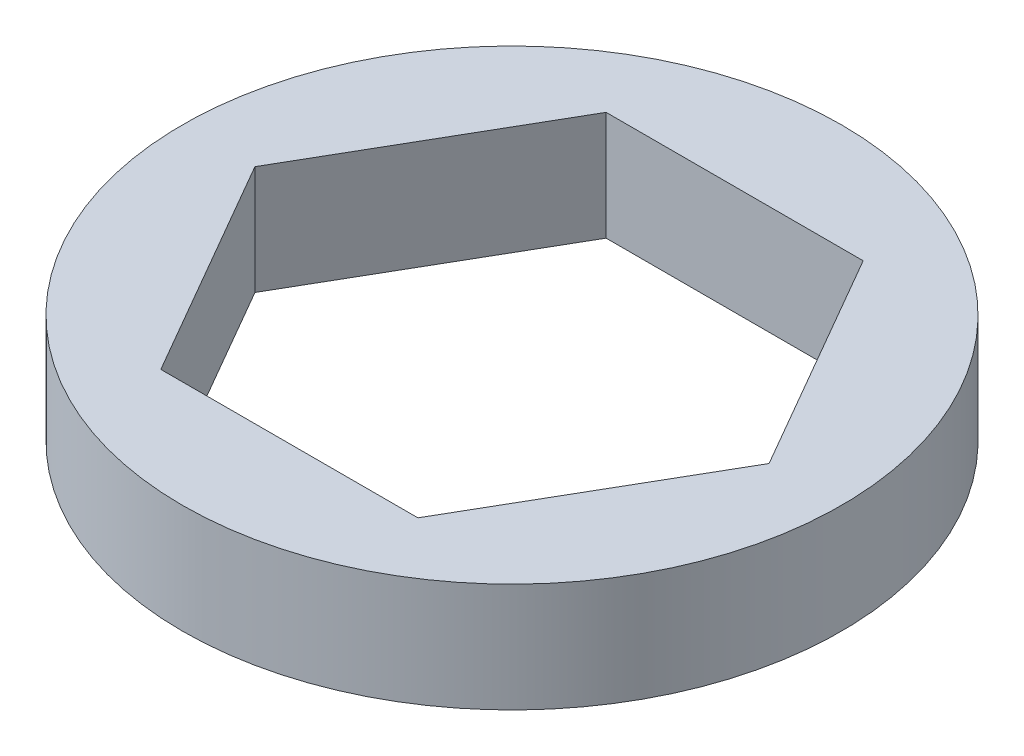
SolidWorks part; units mm, degrees
ref_plane "Front Plane" through (0, 0, 0) normal (0, 0, 1) x (1, 0, 0)
ref_plane "Top Plane" through (0, 0, 0) normal (0, 1, 0) x (1, 0, 0)
ref_plane "Right Plane" through (0, 0, 0) normal (1, 0, 0) x (0, 0, -1)
sketch "Sketch1" plane through (0, 0, 0) normal (0, 1, 0) x (1, 0, 0)
  line L1 (2.7863, -4.826) -> (5.5726, 0)
  line L2 (5.5726, 0) -> (2.7863, 4.826)
  line L3 (2.7863, 4.826) -> (-2.7863, 4.826)
  line L4 (-2.7863, 4.826) -> (-5.5726, 0)
  line L5 (-5.5726, 0) -> (-2.7863, -4.826)
  line L6 (-2.7863, -4.826) -> (2.7863, -4.826)
  circle A0 centre (0, 0) radius 7.1438
  circle A1 centre (0, 0) radius 4.826 construction
  dimension "D1" = 9.652
  dimension "D2" = 14.2875
extrude "Boss-Extrude1" add sketch "Sketch1" along normal mid plane 2.3622
